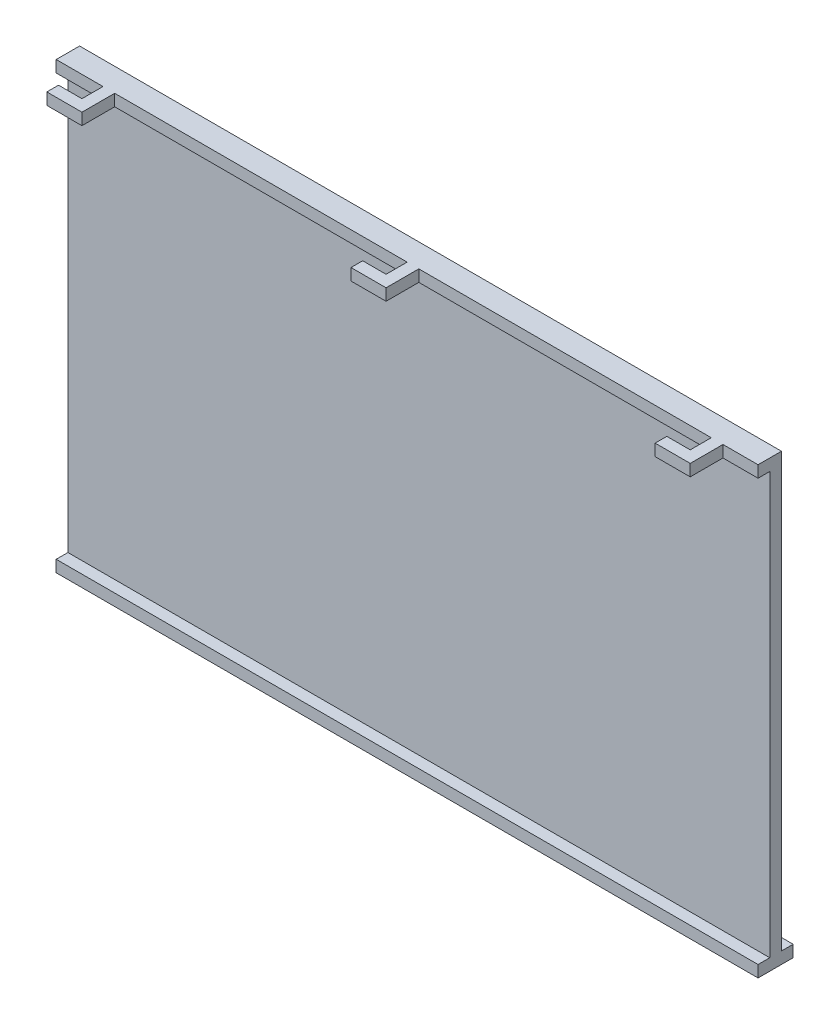
SolidWorks part; units mm, degrees
ref_plane "Front Plane" through (0, 0, 0) normal (0, 0, 1) x (1, 0, 0)
ref_plane "Top Plane" through (0, 0, 0) normal (0, 1, 0) x (1, 0, 0)
ref_plane "Right Plane" through (0, 0, 0) normal (1, 0, 0) x (0, 0, -1)
sketch "Sketch1" plane through (0, 0, 0) normal (1, 0, 0) x (0, 0, -1)
  line L0 (55, 0) -> (-55, 0) construction
  line L1 (-2.5, 0) -> (2.5, 0)
  line L2 (-2.5, 0) -> (-2.5, 190)
  line L3 (-2.5, 190) -> (2.5, 190)
  line L4 (2.5, 0) -> (2.5, 190)
  line L5 (0, 55) -> (0, -55) construction
  line L6 (-2.5, 0) -> (-7.5, 0)
  line L7 (-2.5, 0) -> (-2.5, 5)
  line L8 (-2.5, 5) -> (-7.5, 5)
  line L9 (-7.5, 0) -> (-7.5, 5)
  line L10 (2.5, 0) -> (7.5, 0)
  line L11 (2.5, 0) -> (2.5, 5)
  line L12 (2.5, 5) -> (7.5, 5)
  line L13 (7.5, 0) -> (7.5, 5)
  line L15 (-2.5, 190) -> (-7.5, 190)
  line L16 (-2.5, 190) -> (-2.5, 185)
  line L17 (-2.5, 185) -> (-7.5, 185)
  line L18 (-7.5, 190) -> (-7.5, 185)
  point P12 (0, 190)
  dimension "D1" = 5
  dimension "D2" = 5
  dimension "D3" = 190
  dimension "D4" = 5
  dimension "D5" = 5
  dimension "D6" = 5
  dimension "D7" = 5
extrude "Boss-Extrude1" add sketch "Sketch1" along normal mid plane 300 contours L1 L4 L3 L2 | L15 L18 L17 L2 | L10 L13 L12 L4 | L7 L8 L9 L6
sketch "Sketch2" plane through (0, 190, 0) normal (0, 1, 0) x (1, 0, 0)
  line L0 (135, -7.5) -> (135, -21.5)
  line L1 (150, -7.5) -> (-150, -7.5) construction
  line L2 (135, -21.5) -> (120, -21.5)
  line L3 (120, -21.5) -> (120, -16.5)
  line L4 (120, -16.5) -> (130, -16.5)
  line L5 (130, -16.5) -> (130, -7.5)
  line L6 (130, -7.5) -> (135, -7.5)
  line L7 (150, -7.5) -> (150, 2.5) construction
  line L8 (0, -7.5) -> (5, -7.5)
  line L9 (5, -7.5) -> (5, -21.5)
  line L10 (5, -21.5) -> (-10, -21.5)
  line L11 (-10, -21.5) -> (-10, -16.5)
  line L12 (-10, -16.5) -> (0, -16.5)
  line L13 (0, -16.5) -> (0, -7.5)
  line L14 (-130, -7.5) -> (-125, -7.5)
  line L15 (-125, -7.5) -> (-125, -21.5)
  line L16 (-125, -21.5) -> (-140, -21.5)
  line L17 (-140, -21.5) -> (-140, -16.5)
  line L18 (-140, -16.5) -> (-130, -16.5)
  line L19 (-130, -16.5) -> (-130, -7.5)
  dimension "D1" = 5
  dimension "D2" = 14
  dimension "D3" = 5
  dimension "D4" = 15
  dimension "D5" = 15
  dimension "D6" = 3
extrude "Boss-Extrude2" add sketch "Sketch2" against normal blind 5
